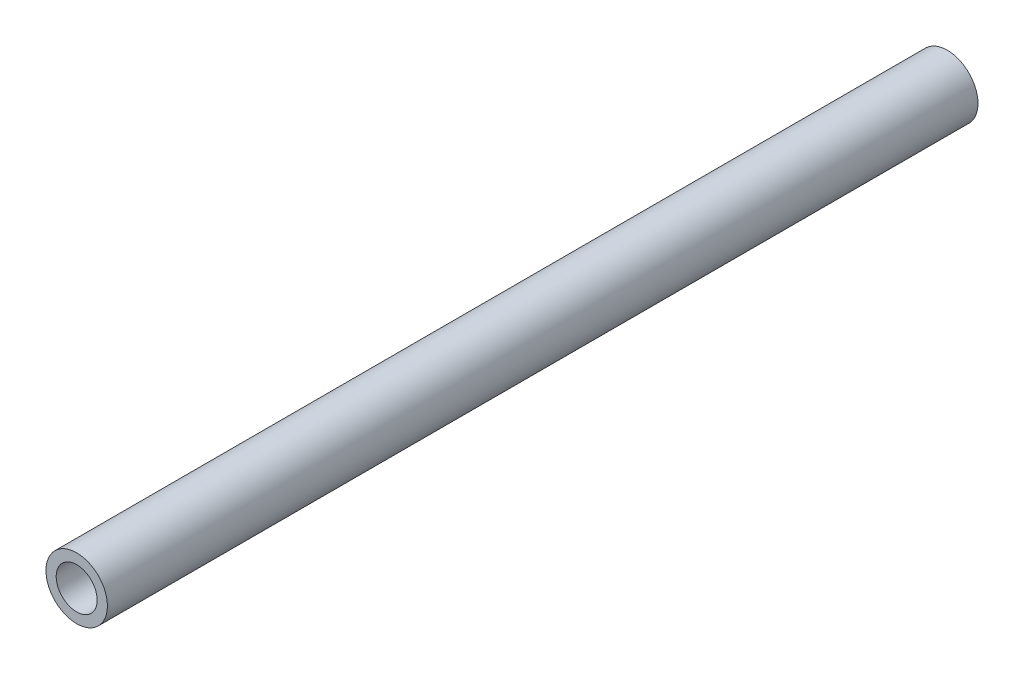
SolidWorks part; units mm, degrees
ref_plane "Front Plane" through (0, 0, 0) normal (0, 0, 1) x (1, 0, 0)
ref_plane "Top Plane" through (0, 0, 0) normal (0, 1, 0) x (1, 0, 0)
ref_plane "Right Plane" through (0, 0, 0) normal (1, 0, 0) x (0, 0, -1)
sketch "Sketch1" plane through (0, 0, 0) normal (0, 0, 1) x (1, 0, 0)
  circle A0 centre (0, 0) radius 3
  circle A1 centre (0, 0) radius 2
  dimension "D1" = 6
  dimension "D2" = 4
extrude "Boss-Extrude1" add sketch "Sketch1" along normal blind 85
